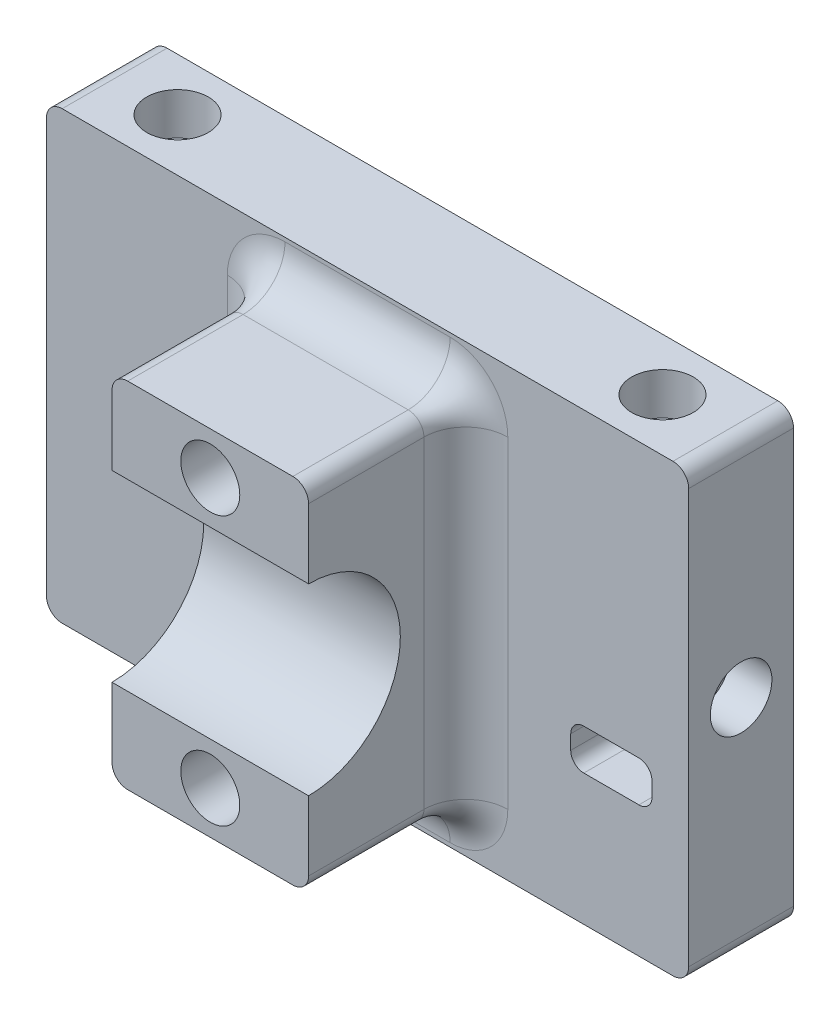
SolidWorks part; units mm, degrees
ref_plane "Plan de face" through (0, 0, 0) normal (0, 0, 1) x (1, 0, 0)
ref_plane "Plan de dessus" through (0, 0, 0) normal (0, 1, 0) x (1, 0, 0)
ref_plane "Plan de droite" through (0, 0, 0) normal (1, 0, 0) x (0, 0, -1)
sketch "Esquisse1" plane through (0, 0, 0) normal (0, 0, 1) x (1, 0, 0)
  line L1 (24.5, 17) -> (-24.5, 17)
  line L2 (24.5, 17) -> (24.5, -17)
  line L3 (24.5, -17) -> (-24.5, -17)
  line L4 (-24.5, 17) -> (-24.5, -17)
  line L5 (24.5, 17) -> (-24.5, -17) construction
  line L6 (24.5, -17) -> (-24.5, 17) construction
  point P0 (0, 0)
  dimension "D1" = 49
  dimension "D2" = 34
extrude "Base" add sketch "Esquisse1" along normal blind 8
sketch "Esquisse2" plane through (-24.5, 0, 0) normal (-1, 0, 0) x (0, 0, 1)
  line L0 (8, -17) -> (0, -17) construction
  circle A0 centre (4, 0) radius 2.35
  point P5 (4, -17)
  dimension "D1" = 4.7
sketch "Esquisse3" plane through (24.5, 0, 0) normal (1, 0, 0) x (0, 0, -1)
  circle A0 centre (-4, 0) radius 2.35
  circle A1 centre (-4, 0) radius 2.35 construction
extrude "Insert_M3_L" cut sketch "Esquisse2" against normal blind 3.2 contours A0
extrude "Insert_M3_R" cut sketch "Esquisse3" against normal blind 3.2
sketch "Esquisse4" plane through (0, 17, 0) normal (0, 1, 0) x (1, 0, 0)
  line L0 (-24.5, -8) -> (-24.5, 0) construction
  line L1 (24.5, -8) -> (24.5, 0) construction
  circle A0 centre (-18.5, -4) radius 2.35
  circle A1 centre (18.5, -4) radius 2.35
  point P9 (-24.5, -4)
  dimension "D3" = 4.7
  dimension "D1" = 6
  dimension "D2" = 6
sketch "Esquisse5" plane through (0, -17, -17) normal (0, 1, 0) x (1, 0, 0)
  circle A0 centre (-18.5, -21) radius 2.35
  circle A1 centre (18.5, -21) radius 2.35
  dimension "D3" = 4.7
extrude "Insert_M3_TOP" cut sketch "Esquisse4" against normal blind 3.2
extrude "Inser_M3_BOT" cut sketch "Esquisse5" along normal blind 3.2
sketch "Esquisse11" plane through (-21.3, 0, 0) normal (-1, 0, 0) x (0, 0, 1)
  circle A0 centre (4, 0) radius 1.5
  dimension "D1" = 3
extrude "Passage_Vis_L" cut sketch "Esquisse11" against normal blind 5
sketch "Esquisse12" plane through (21.3, 0, 0) normal (1, 0, 0) x (0, 0, -1)
  circle A0 centre (-4, 0) radius 1.5
  dimension "D1" = 3
extrude "Passage_Vis_R" cut sketch "Esquisse12" against normal blind 5
sketch "Esquisse10" plane through (0, 13.8, 0) normal (0, 1, 0) x (1, 0, 0)
  circle A0 centre (-18.5, -4) radius 1.5
  circle A1 centre (18.5, -4) radius 1.5
  dimension "D1" = 3
extrude "Passage_Vis_TOP" cut sketch "Esquisse10" against normal blind 5
sketch "Esquisse13" plane through (0, -13.8, 0) normal (0, -1, 0) x (1, 0, 0)
  circle A0 centre (-18.5, 4) radius 1.5
  circle A1 centre (18.5, 4) radius 1.5
  dimension "D1" = 3
extrude "Passage_Vis_BOT" cut sketch "Esquisse13" against normal blind 5
fillet "Congé1" radius 1.2 4 edges at (-24.5, -17, 4) (24.5, -17, 4) (24.5, 17, 4) (-24.5, 17, 4)
chamfer "Chanfrein1" [suppressed] distance 1 angle 45
sketch "Esquisse6" plane through (0, 0, 8) normal (0, 0, 1) x (1, 0, 0)
  line L1 (7.5, 13.5) -> (-7.5, 13.5)
  line L2 (7.5, 13.5) -> (7.5, -13.5)
  line L3 (7.5, -13.5) -> (-7.5, -13.5)
  line L4 (-7.5, 13.5) -> (-7.5, -13.5)
  line L5 (7.5, 13.5) -> (-7.5, -13.5) construction
  line L6 (7.5, -13.5) -> (-7.5, 13.5) construction
  point P0 (0, 0)
  dimension "D1" = 15
  dimension "D2" = 27
extrude "Support_Fixation" add sketch "Esquisse6" along normal blind 12
sketch "Esquisse7" plane through (-7.5, 0, 0) normal (-1, 0, 0) x (0, 0, 1)
  line L0 (20, 13.5) -> (20, -13.5) construction
  line L1 (20, 7) -> (20, -7)
  arc A0 (20, 7) -> (20, -7) centre (20, 0) ccw
  dimension "D1" = 7
extrude "Passage_Guidon" cut sketch "Esquisse7" against normal up to next
fillet "Congé_Vertical" radius 1.2 4 edges at (-7.5, 13.5, 14) (7.5, 13.5, 14) (7.5, -13.5, 14) (-7.5, -13.5, 14)
fillet "Congé_Base" radius 3.2 8 edges at (-7.1485, -13.1485, 8) (-7.5, 0, 8) (-7.1485, 13.1485, 8) (0, 13.5, 8) (7.1485, 13.1485, 8) (7.5, 0, 8) (7.1485, -13.1485, 8) (0, -13.5, 8)
sketch "Esquisse8" plane through (0, 0, 20) normal (0, 0, 1) x (1, 0, 0)
  line L1 (7.5, 7) -> (-7.5, 7) construction
  line L2 (11, 0) -> (-11, 0) construction
  line L3 (6.3, 13.5) -> (-6.3, 13.5) construction
  circle A0 centre (0, 10.25) radius 2.25
  circle A1 centre (0, -10.25) radius 2.25
  point P17 (0, 13.5)
  dimension "D1" = 4.5
  dimension "D2" = 3.25
extrude "Inserts_M3_Fixation" cut sketch "Esquisse8" against normal blind 3.2
chamfer "Chanfrein_Fixation" [suppressed] distance 0.4 angle 45
sketch "Esquisse9" plane through (0, 0, 16.8) normal (0, 0, 1) x (1, 0, 0)
  line L0 (11, 0) -> (-11, 0) construction
  circle A0 centre (0, 10.25) radius 1.5
  circle A1 centre (0, -10.25) radius 1.5
  dimension "D1" = 3
extrude "Passage_Vis_Fixation" cut sketch "Esquisse9" against normal blind 5
sketch "Esquisse14" plane through (0, 0, 8) normal (0, 0, 1) x (1, 0, 0)
  line L0 (-23.3, -17) -> (23.3, -17) construction
  line L1 (16.5, -3.9) -> (20.7, -3.9)
  line L2 (15.5, -4.9) -> (15.5, -6)
  line L3 (16.5, -7) -> (20.7, -7)
  line L4 (21.7, -4.9) -> (21.7, -6)
  line L5 (7.5, -12.3) -> (7.5, 12.3) construction
  arc A2 (20.7, -3.9) -> (21.7, -4.9) centre (20.7, -4.9) cw
  arc A3 (20.7, -7) -> (21.7, -6) centre (20.7, -6) ccw
  arc A4 (15.5, -6) -> (16.5, -7) centre (16.5, -6) ccw
  arc A5 (16.5, -3.9) -> (15.5, -4.9) centre (16.5, -4.9) ccw
  point P10 (21.7, -3.9)
  point P13 (21.7, -7)
  point P18 (15.5, -3.9)
  dimension "D5" = 1
  dimension "D1" = 6.2
  dimension "D2" = 3.1
  dimension "D3" = 10
  dimension "D4" = 8
extrude "Passe_Cable" cut sketch "Esquisse14" against normal blind 8 contours L4 L1 L2 L3
